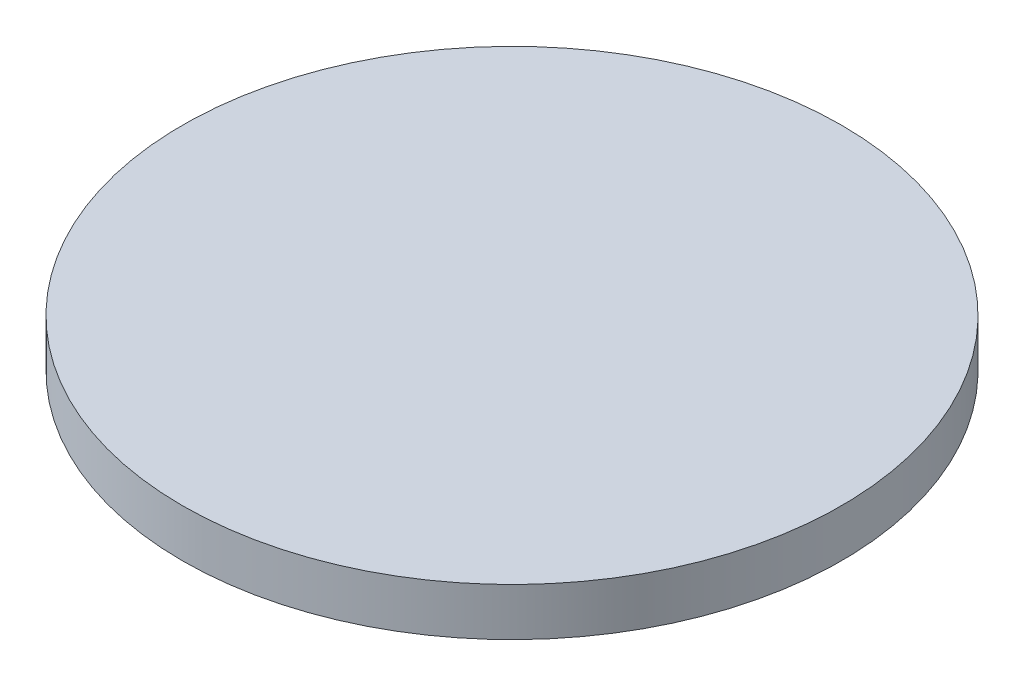
SolidWorks part; units mm, degrees
material "OMD-98"
ref_plane "Front Plane" through (0, 0, 0) normal (0, 0, 1) x (1, 0, 0)
ref_plane "Top Plane" through (0, 0, 0) normal (0, 1, 0) x (1, 0, 0)
ref_plane "Right Plane" through (0, 0, 0) normal (1, 0, 0) x (0, 0, -1)
sketch "Sketch1" plane through (0, 0, 0) normal (0, 1, 0) x (1, 0, 0)
  circle A0 centre (0, 0) radius 6.9
  dimension "D1" = 13.8
extrude "Boss-Extrude1" add sketch "Sketch1" along normal blind 1
